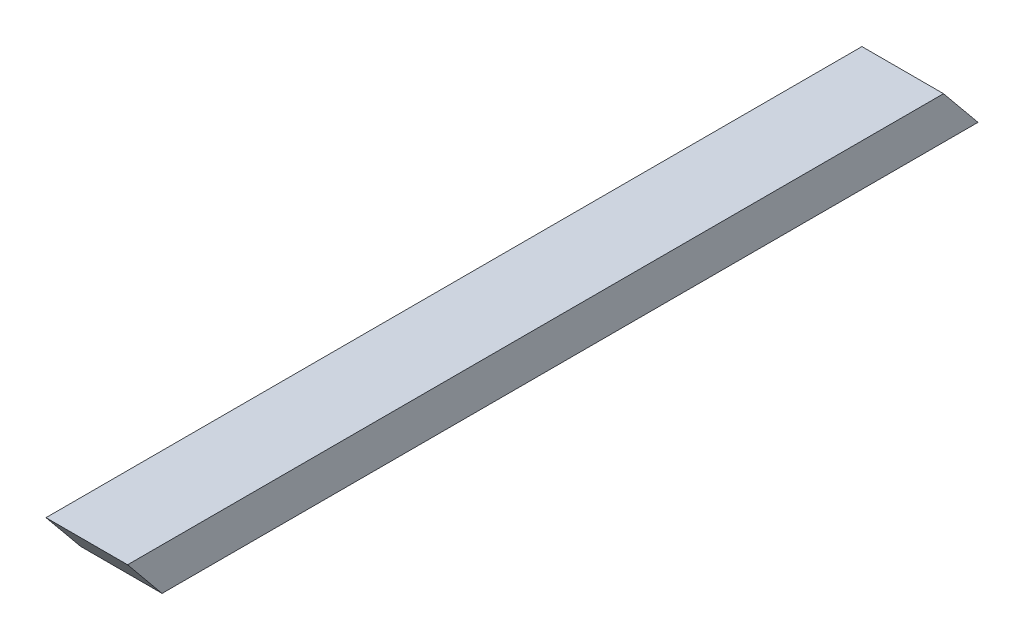
SolidWorks part; units mm, degrees
ref_plane "Front" through (0, 0, 0) normal (0, 0, 1) x (1, 0, 0)
ref_plane "Top" through (0, 0, 0) normal (0, 1, 0) x (1, 0, 0)
ref_plane "Right" through (0, 0, 0) normal (1, 0, 0) x (0, 0, -1)
sketch "Sketch1" plane through (0, 0, 0) normal (1, 0, 0) x (0, 0, -1)
  line L0 (-155.9416, 38.4) -> (-143.2667, 22.9292)
  line L1 (-143.2667, 22.9292) -> (156.7333, 22.9292)
  line L2 (156.7333, 22.9292) -> (144.0584, 38.4)
  line L3 (-155.9416, 38.4) -> (144.0584, 38.4)
  point P2 (184.8584, -11.4)
  point P5 (0, 0)
  dimension "D1" = 300
  dimension "D2" = 20
extrude "Boss-Extrude1" add sketch "Sketch1" along normal blind 30
